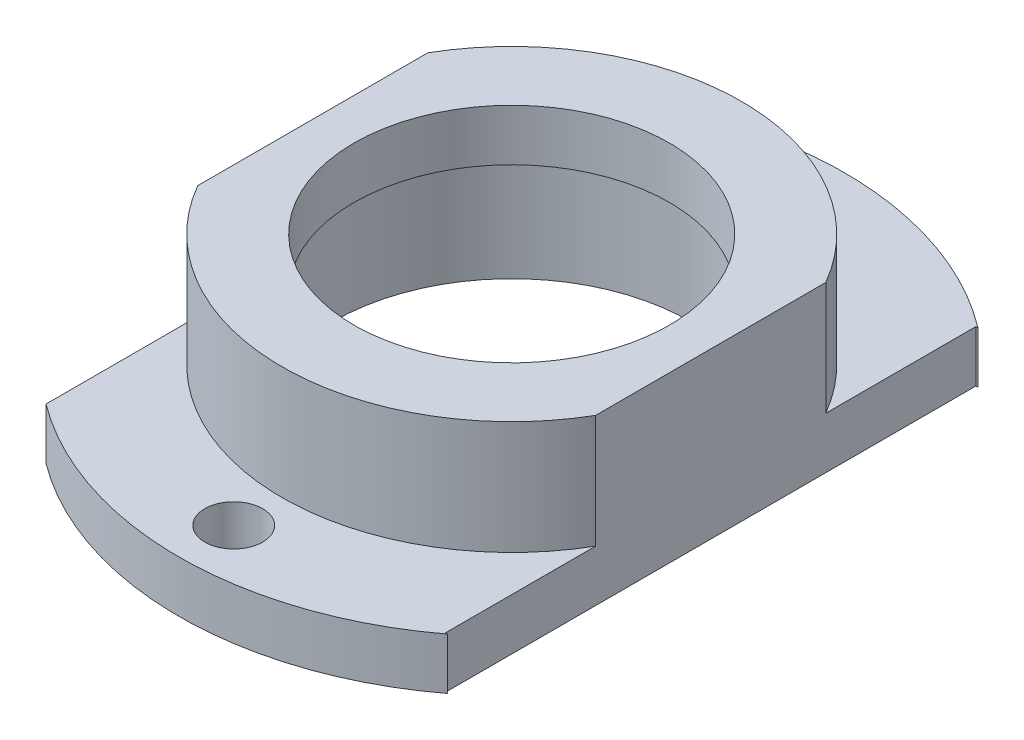
SolidWorks part; units mm, degrees
ref_plane "Front Plane" through (0, 0, 0) normal (0, 0, 1) x (1, 0, 0)
ref_plane "Top Plane" through (0, 0, 0) normal (0, 1, 0) x (1, 0, 0)
ref_plane "Right Plane" through (0, 0, 0) normal (1, 0, 0) x (0, 0, -1)
sketch "Sketch1" plane through (0, 0, 0) normal (0, 0, 1) x (1, 0, 0)
  line L0 (0, 0) -> (9.525, 0)
  line L1 (9.525, 0) -> (9.525, 3.175)
  line L2 (9.525, 3.175) -> (3.175, 3.175)
  line L3 (3.175, 3.175) -> (3.175, 10.16)
  line L4 (3.175, 10.16) -> (-1.27, 10.16)
  line L5 (-1.27, 10.16) -> (-1.27, 6.985)
  line L6 (-1.27, 6.985) -> (0, 6.985)
  line L7 (0, 6.985) -> (0, 0)
  line L8 (-10.9982, 23.0744) -> (-10.9982, 9.3985) construction
  point P11 (6.35, 3.175)
  dimension "D1" = 9.7282
  dimension "D2" = 10.9982
  dimension "D3" = 3.175
  dimension "D4" = 3.175
  dimension "D5" = 3.175
  dimension "D6" = 9.525
  dimension "D7" = 6.985
revolve "Revolve2" add sketch "Sketch1" angle 360 about L8
sketch "Sketch2" plane through (0, 10.16, 0) normal (0, 1, 0) x (1, 0, 0)
  line L6 (-23.2664, 0) -> (-10.9982, 0) construction
  line L11 (-32.6522, 17.1685) -> (-23.2664, 17.1685)
  line L12 (-32.6522, 17.1685) -> (-32.6522, -17.1685)
  line L13 (-32.6522, -17.1685) -> (-23.2664, -17.1685)
  line L14 (-23.2664, 17.1685) -> (-23.2664, -17.1685)
  line L15 (17.6967, 16.3523) -> (1.27, 16.3523)
  line L16 (17.6967, 16.3523) -> (17.6967, -16.3523)
  line L17 (17.6967, -16.3523) -> (1.27, -16.3523)
  line L18 (1.27, 16.3523) -> (1.27, -16.3523)
  line L19 (-10.9982, 0) -> (1.27, 0) construction
  dimension "D1" = 1.27
extrude "Cut-Extrude1" cut sketch "Sketch2" against normal up to surface (10.16 mm away) contours L13 L14 L11 L12 | L17 L18 L15 L16 up to face at (-31.5214, 0, 0)
sketch "Sketch3" plane through (0, 3.175, 0) normal (0, 1, 0) x (1, 0, 0)
  line L0 (-10.9982, 17.145) -> (-10.9982, 0) construction
  line L1 (-10.9982, 0) -> (0, 0) construction
  line L3 (-10.9982, 0) -> (-10.9982, -17.145) construction
  line L4 (-10.9982, 0) -> (1.27, 7.0972) construction
  line L5 (-10.9982, 0) -> (-23.2664, 7.0972) construction
  circle A0 centre (-10.9982, 17.145) radius 1.7859
  circle A1 centre (-10.9982, -17.145) radius 1.7859
  dimension "D1" = 3.5719
  dimension "D2" = 3.5719
  dimension "D3" = 17.145
extrude "Cut-Extrude2" cut sketch "Sketch3" against normal up to next
